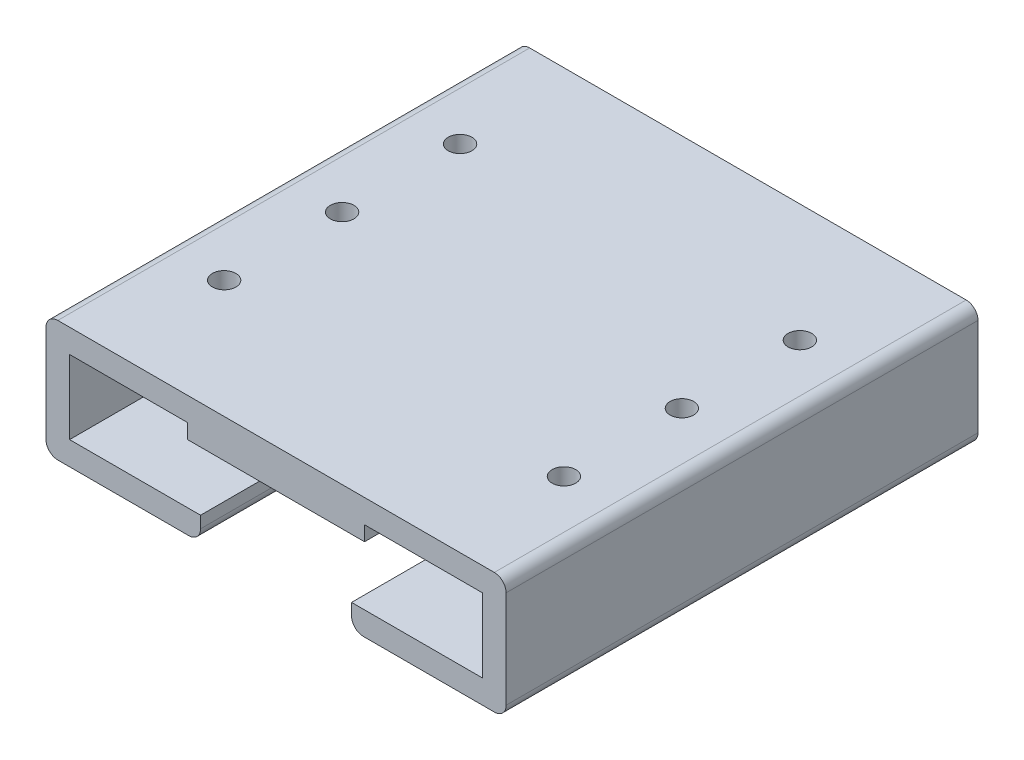
SolidWorks part; units mm, degrees
ref_plane "Front Plane" through (0, 0, 0) normal (0, 0, 1) x (1, 0, 0)
ref_plane "Top Plane" through (0, 0, 0) normal (0, 1, 0) x (1, 0, 0)
ref_plane "Right Plane" through (0, 0, 0) normal (1, 0, 0) x (0, 0, -1)
sketch "Sketch1" plane through (0, 0, 0) normal (0, 0, 1) x (1, 0, 0)
  line L0 (-15, 0) -> (15, 0)
  line L1 (0, 0) -> (0, 24.9176) construction
  line L2 (-15, 0) -> (-15, 2.5)
  line L3 (-15, 2.5) -> (-35, 2.5)
  line L4 (-35, 2.5) -> (-35, -10)
  line L5 (-35, -10) -> (-12.8, -10)
  line L6 (-15, 6.5) -> (-37, 6.5)
  line L7 (-39, 4.5) -> (-39, -12)
  line L8 (-37, -14) -> (-14.8, -14)
  line L9 (-15, 6.5) -> (15, 6.5)
  line L10 (-39, 6.5) -> (-39, -14) construction
  line L11 (-39, -14) -> (-12.8, -14) construction
  line L12 (-15, 6.5) -> (-39, 6.5) construction
  line L13 (-12.8, -10) -> (-12.8, -12)
  line L14 (15, 0) -> (15, 2.5)
  line L15 (15, 2.5) -> (35, 2.5)
  line L16 (35, 2.5) -> (35, -10)
  line L17 (35, -10) -> (12.8, -10)
  line L18 (12.8, -10) -> (12.8, -12)
  line L19 (37, -14) -> (14.8, -14)
  line L20 (39, 4.5) -> (39, -12)
  line L21 (15, 6.5) -> (37, 6.5)
  arc A0 (-39, -12) -> (-37, -14) centre (-37, -12) ccw
  arc A1 (-37, 6.5) -> (-39, 4.5) centre (-37, 4.5) ccw
  arc A2 (-14.8, -14) -> (-12.8, -12) centre (-14.8, -12) ccw
  arc A3 (14.8, -14) -> (12.8, -12) centre (14.8, -12) cw
  arc A4 (39, -12) -> (37, -14) centre (37, -12) cw
  arc A5 (37, 6.5) -> (39, 4.5) centre (37, 4.5) cw
  point P4 (0, 0)
  point P38 (0, 6.5)
  dimension "D7" = 2
  dimension "D8" = 2
  dimension "D1" = 30
  dimension "D2" = 2.5
  dimension "D3" = 20
  dimension "D4" = 12.5
  dimension "D5" = 22.2
  dimension "D6" = 4
extrude "Boss-Extrude1" add sketch "Sketch1" along normal blind 80
sketch "Sketch2" plane through (0, 2.5, 0) normal (0, -1, 0) x (1, 0, 0)
  line L0 (-35, 80) -> (-15, 80) construction
  line L1 (-35, 80) -> (-35, 0) construction
  circle A0 centre (-28.8, 60) radius 2
  circle A1 centre (28.8, 60) radius 2
  circle A2 centre (28.8, 40) radius 2
  circle A3 centre (28.8, 20) radius 2
  circle A4 centre (-28.8, 40) radius 2
  circle A5 centre (-28.8, 20) radius 2
  dimension "D1" = 20
  dimension "D2" = 6.2
  dimension "D3" = 2
  dimension "D4" = 3
extrude "Cut-Extrude1" cut sketch "Sketch2" against normal blind 4
sketch "Sketch3" plane through (0, -10, 0) normal (0, 1, 0) x (1, 0, 0)
  line L0 (35, -80) -> (35, 0) construction
  line L1 (35, -80) -> (12.8, -80) construction
  circle A0 centre (28.8, -40) radius 2
  dimension "D1" = 6.2
  dimension "D2" = 40
extrude "Cut-Extrude2" cut sketch "Sketch3" against normal blind 4
